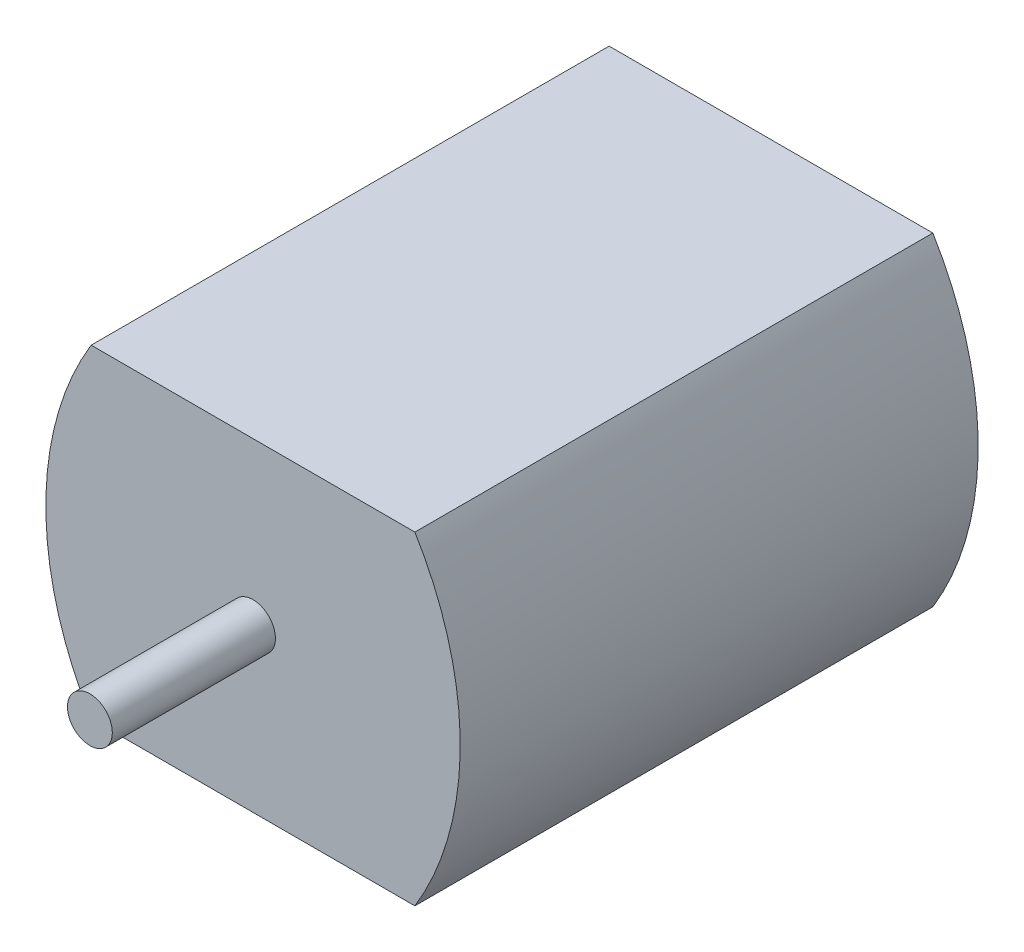
SolidWorks part; units mm, degrees
ref_plane "Front Plane" through (0, 0, 0) normal (0, 0, 1) x (1, 0, 0)
ref_plane "Top Plane" through (0, 0, 0) normal (0, 1, 0) x (1, 0, 0)
ref_plane "Right Plane" through (0, 0, 0) normal (1, 0, 0) x (0, 0, -1)
sketch "Sketch1" plane through (0, 0, 0) normal (0, 0, 1) x (1, 0, 0)
  line L1 (0, 0) -> (-15.875, 0)
  line L3 (0, 15.875) -> (-15.875, 15.875)
  arc A0 (-15.875, 0) -> (-15.875, 15.875) centre (-2.8121, 7.9375) cw
  arc A1 (0, 0) -> (0, 15.875) centre (-13.0629, 7.9375) ccw
  point P0 (-18.0975, 7.9375)
  point P2 (2.2225, 7.9375)
  point P9 (0, 0)
  point P10 (0, 0)
  dimension "D1" = 15.875
  dimension "D2" = 15.875
  dimension "D3" = 20.32
  dimension "D4" = 15.875
extrude "Boss-Extrude1" add sketch "Sketch1" along normal blind 25.4
sketch "Sketch2" plane through (0, 0, 25.4) normal (0, 0, 1) x (1, 0, 0)
  line L0 (0, 15.875) -> (-15.875, 15.875) construction
  circle A0 centre (-7.9375, 7.9375) radius 1.1
  arc A1 (0, 0) -> (0, 15.875) centre (-13.0629, 7.9375) ccw construction
  point P2 (-7.9375, 15.875)
  point P3 (2.2225, 7.9375)
  point P6 (0, 0)
  point P10 (0, 0)
  dimension "D1" = 2.2
extrude "Boss-Extrude2" add sketch "Sketch2" along normal blind 8
equation "\"D1@Sketch1\"=\"D2@Sketch1\""
equation "\"D4@Sketch1\"=\"D2@Sketch1\""
